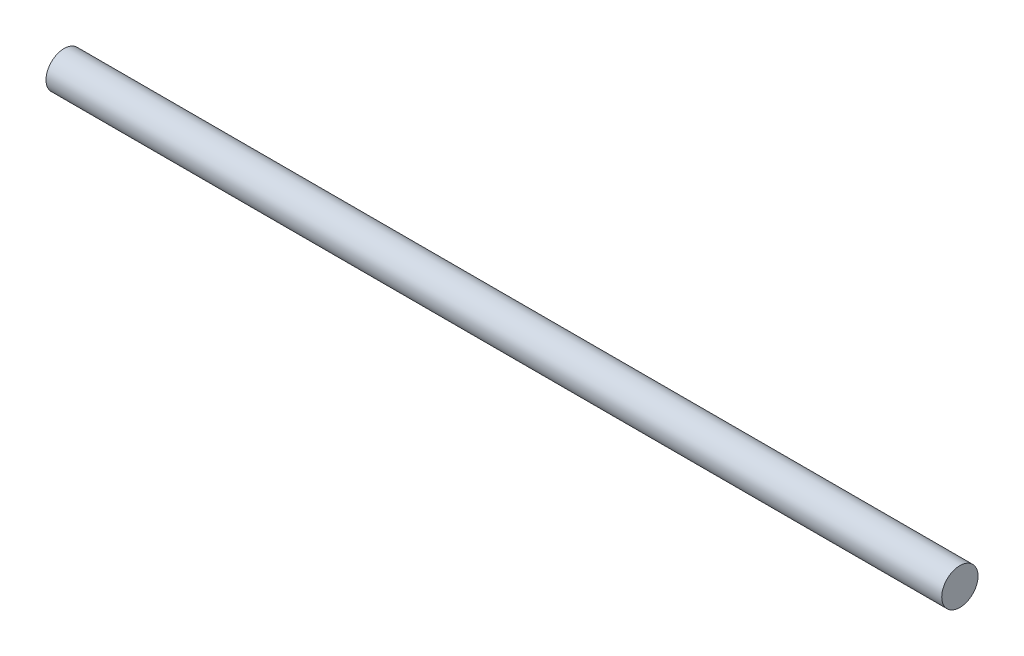
SolidWorks part; units mm, degrees
ref_plane "Plan de face" through (0, 0, 0) normal (0, 0, 1) x (1, 0, 0)
ref_plane "Plan de dessus" through (0, 0, 0) normal (0, 1, 0) x (1, 0, 0)
ref_plane "Plan de droite" through (0, 0, 0) normal (1, 0, 0) x (0, 0, -1)
sketch "Esquisse1" plane through (0, 0, 0) normal (0, 0, 1) x (1, 0, 0)
  line L0 (-23.9082, 0) -> (50.0918, 0)
  dimension "D1" = 74
revolve "Révol.-Mince1" add sketch "Esquisse1" angle 360 about L0 wall 1.5
